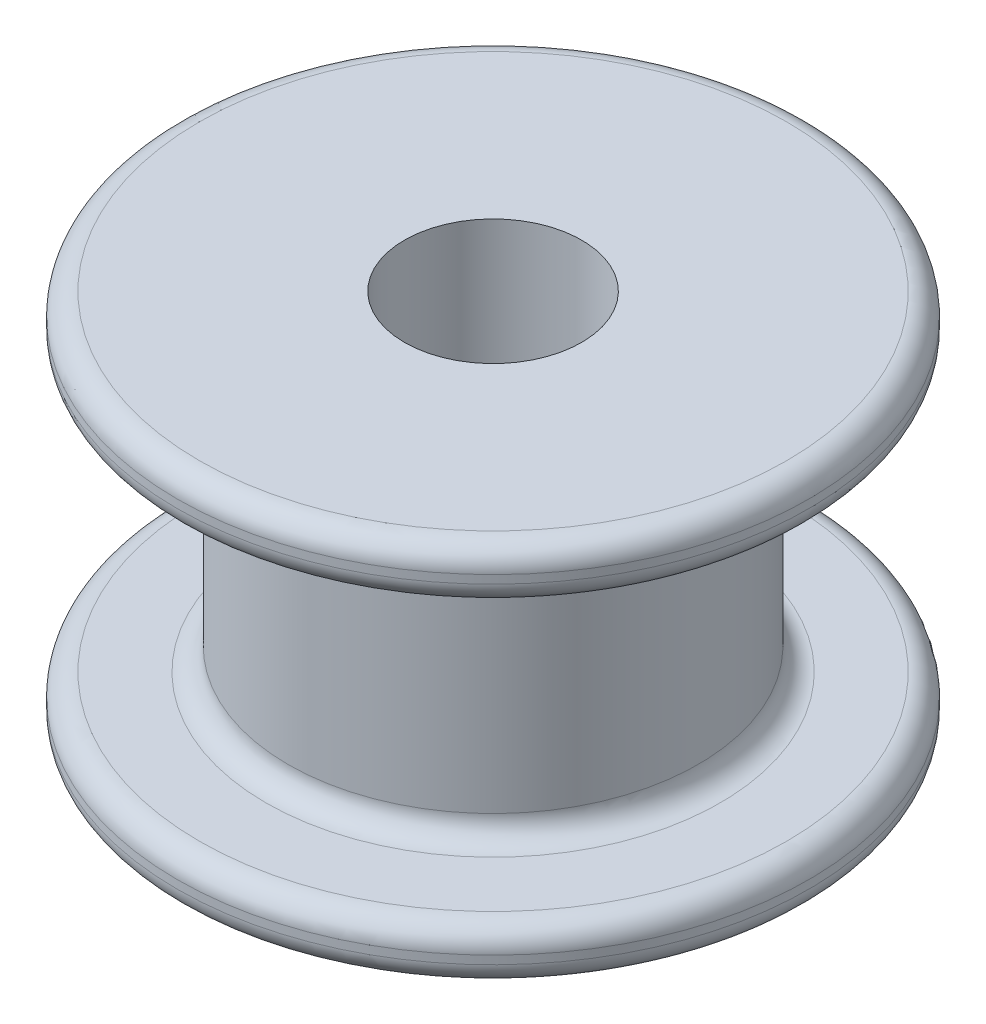
SolidWorks part; units mm, degrees
ref_plane "Front Plane" through (0, 0, 0) normal (0, 0, 1) x (1, 0, 0)
ref_plane "Top Plane" through (0, 0, 0) normal (0, 1, 0) x (1, 0, 0)
ref_plane "Right Plane" through (0, 0, 0) normal (1, 0, 0) x (0, 0, -1)
sketch "Sketch3" plane through (0, 0, 0) normal (1, 0, 0) x (0, 0, -1)
  line L0 (8, 0) -> (8, 17.25)
  line L1 (8, 17.25) -> (26.5, 17.25)
  line L2 (28.5, 15.25) -> (28.5, 14.5)
  line L3 (26.5, 12.5) -> (20.5, 12.5)
  line L4 (18.5, 10.5) -> (18.5, 0)
  line L5 (18.5, 0) -> (8, 0)
  arc A0 (20.5, 12.5) -> (18.5, 10.5) centre (20.5, 10.5) ccw
  arc A1 (28.5, 14.5) -> (26.5, 12.5) centre (26.5, 14.5) cw
  arc A2 (28.5, 15.25) -> (26.5, 17.25) centre (26.5, 15.25) ccw
  point P10 (18.5, 12.5)
  point P13 (28.5, 12.5)
  point P16 (28.5, 17.25)
  dimension "D6" = 2
  dimension "D1" = 17.25
  dimension "D2" = 20.5
  dimension "D3" = 10
  dimension "D4" = 8
  dimension "D5" = 4.75
ref_axis "Axis1" through (0, 18.1125, 0) along (0, -1, 0)
revolve "Revolve1" add sketch "Sketch3" angle 360 about axis through (0, 18.1125, 0) along (0, -1, 0)
mirror "Mirror1" about plane through (0, 0, -18.5) normal (0, 1, 0) of "Revolve1"
